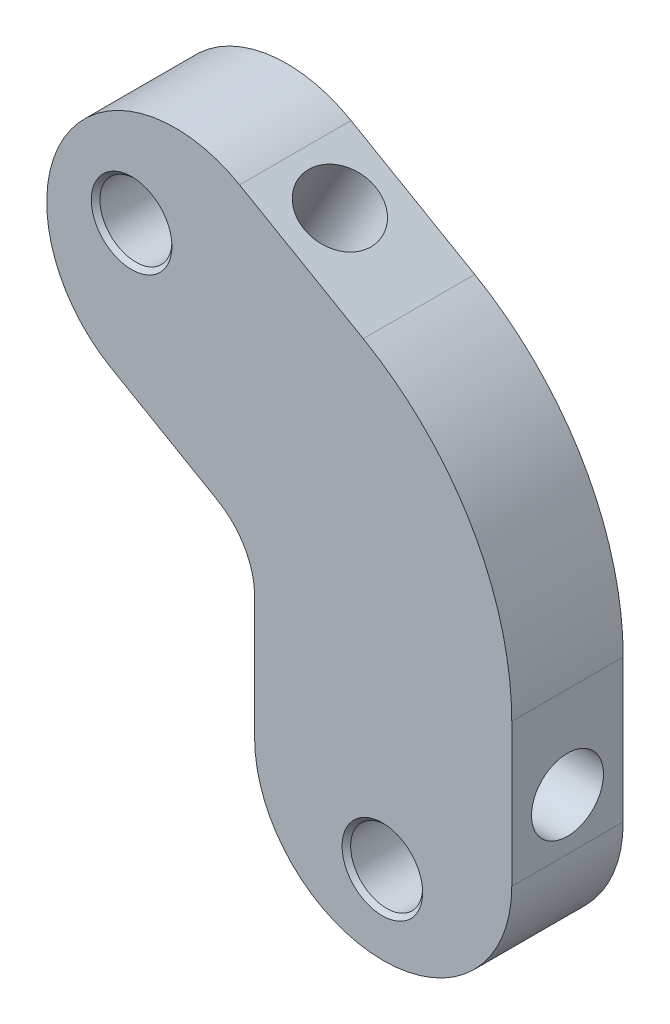
SolidWorks part; units mm, degrees
material "ABS"
ref_plane "Front Plane" through (0, 0, 0) normal (0, 0, 1) x (1, 0, 0)
ref_plane "Top Plane" through (0, 0, 0) normal (0, 1, 0) x (1, 0, 0)
ref_plane "Right Plane" through (0, 0, 0) normal (1, 0, 0) x (0, 0, -1)
ref_plane "Plane4" through (0, 0, 0) normal (0, 0, -1) x (-1, 0, 0)
sketch "Sketch1" plane through (0, 0, 0) normal (0, 0, -1) x (-1, 0, 0)
  line L1 (-15, -11.3397) -> (-15, -28)
  line L5 (15, -28) -> (15, -13.6603)
  line L7 (19.3301, -6.1603) -> (31.7487, 1.0096)
  line L11 (16.7487, 26.9904) -> (2.3205, 18.6603)
  arc A0 (15, -13.6603) -> (19.3301, -6.1603) centre (23.6603, -13.6603) cw
  arc A1 (2.3205, 18.6603) -> (-15, -11.3397) centre (19.641, -11.3397) ccw
  arc A2 (-15, -28) -> (15, -28) centre (0, -28) ccw
  arc A3 (31.7487, 1.0096) -> (39.2487, 14) centre (24.2487, 14) ccw
  arc A4 (31.7487, 26.9904) -> (16.7487, 26.9904) centre (24.2487, 14) ccw
  arc A5 (39.2487, 14) -> (31.7487, 26.9904) centre (24.2487, 14) ccw
  dimension "D3" = 30
  dimension "D1" = 30
  dimension "D2" = 30
extrude "Boss-Extrude1" add sketch "Sketch1" against normal blind 13
sketch "Sketch2" plane through (-7.5, -12.9904, 0) normal (-0.5, -0.866, 0) x (0.866, -0.5, 0)
  line L1 (-28, 0) -> (-11.3397, 0) construction
  arc A0 (-25.0212, 9.4176) -> (-18.9788, 9.4176) centre (-22, 6.5) ccw
  arc A1 (-18.9788, 9.4176) -> (-25.0212, 9.4176) centre (-22, 6.5) ccw
  dimension "D2" = 4.2
  dimension "D1" = 6.5
extrude "Cut-Extrude1" cut sketch "Sketch2" against normal through all
sketch "Sketch3" plane through (-15, 0, 0) normal (-1, 0, 0) x (0, 0, 1)
  line L0 (0, -11.3397) -> (0, -28) construction
  arc A0 (9.4176, -18.9788) -> (9.4176, -25.0212) centre (6.5, -22) ccw
  arc A1 (9.4176, -25.0212) -> (9.4176, -18.9788) centre (6.5, -22) ccw
  dimension "D1" = 6.5
extrude "Cut-Extrude2" cut sketch "Sketch3" against normal through all
hole_wizard "Ø8.4 (8.4) Diameter Hole1" positions "Sketch5" profile "Sketch4" hole size "Ø8.4" standard "ANSI Metric" end condition through all
sketch "Sketch5" plane through (0, 0, 0) normal (0, 0, -1) x (-1, 0, 0)
  line L0 (16.1603, -9.3301) -> (-10.359, 5.9808)
  arc A0 (19.3301, -6.1603) -> (15, -13.6603) centre (23.6603, -13.6603) ccw construction
  arc A1 (2.3205, 18.6603) -> (-15, -11.3397) centre (19.641, -11.3397) ccw construction
  point P0 (29.3474, 16.8312)
  point P1 (0.0974, -33.8312)
  dimension "D1" = 29.25
  dimension "D2" = 29.25
sketch "Sketch4" plane through (-29.3474, 16.8312, 0) normal (1, 0, 0) x (0, 1, 0)
  line L0 (0, 0) -> (0, 13)
  line L1 (0, 13) -> (4.2, 13)
  line L2 (4.2, 13) -> (4.2, 0)
  line L5 (4.2, 0) -> (0, 0)
  line L11 (0, -6.35) -> (0, 107.95) construction
  dimension "Thru Hole Dia." = 8.4
  dimension "Thru Hole Depth" = 13
chamfer "Chamfer2" distance 0.5 angle 45 4 edges at (-0.0974, -29.6312, 0) (-29.3474, 21.0312, 0) (-29.3474, 21.0312, 13) (-0.0974, -29.6312, 13)
